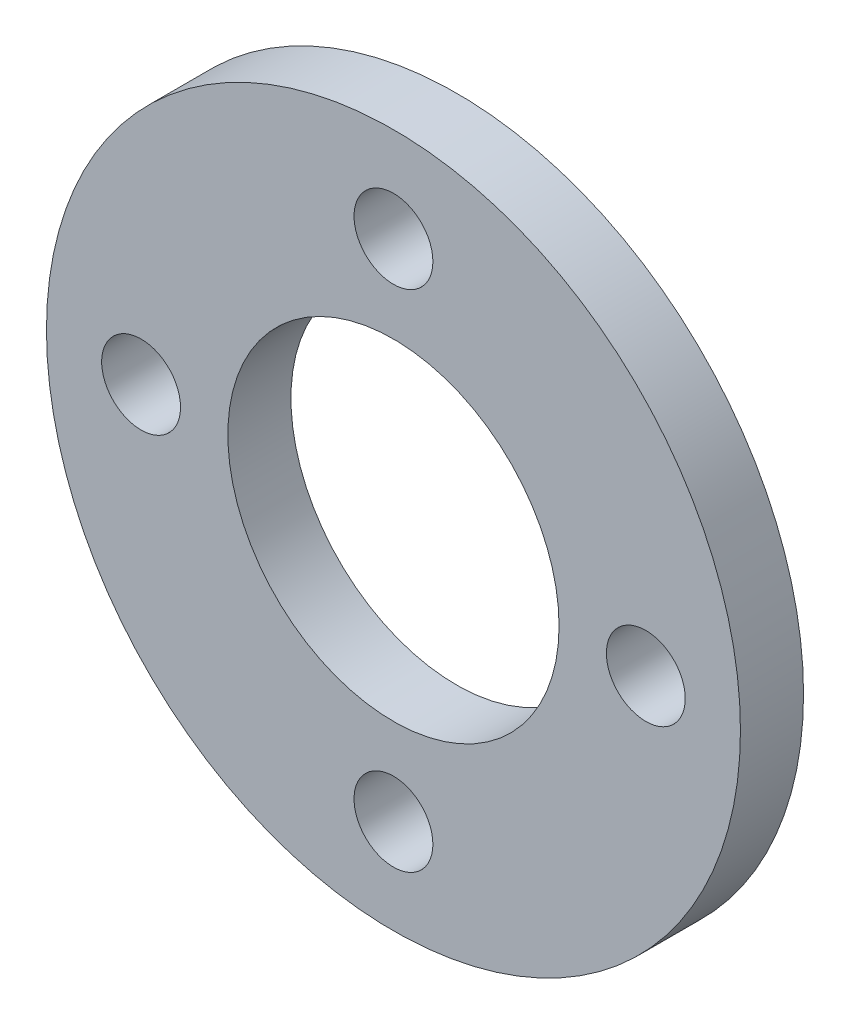
SolidWorks part; units mm, degrees
material "6061-T4 (SS)"
ref_plane "前视基准面" through (0, 0, 0) normal (0, 0, 1) x (1, 0, 0)
ref_plane "上视基准面" through (0, 0, 0) normal (0, 1, 0) x (1, 0, 0)
ref_plane "右视基准面" through (0, 0, 0) normal (1, 0, 0) x (0, 0, -1)
other "Configuration Table"
sketch "草图1" plane through (0, 0, 0) normal (0, 0, 1) x (1, 0, 0)
  circle A0 centre (0, 0) radius 5.25
  circle A1 centre (0, 0) radius 8 construction
  circle A2 centre (0, 0) radius 11
  circle A3 centre (0, 8) radius 1.25
  circle A4 centre (8, 0) radius 1.25
  circle A5 centre (0, -8) radius 1.25
  circle A6 centre (-8, 0) radius 1.25
  point P16 (0, 0)
  dimension "D1" = 10.5
  dimension "D2" = 16
  dimension "D3" = 22
  dimension "D4" = 2.5
  dimension "D5" = 4
extrude "凸台-拉伸1" add sketch "草图1" along normal blind 2
